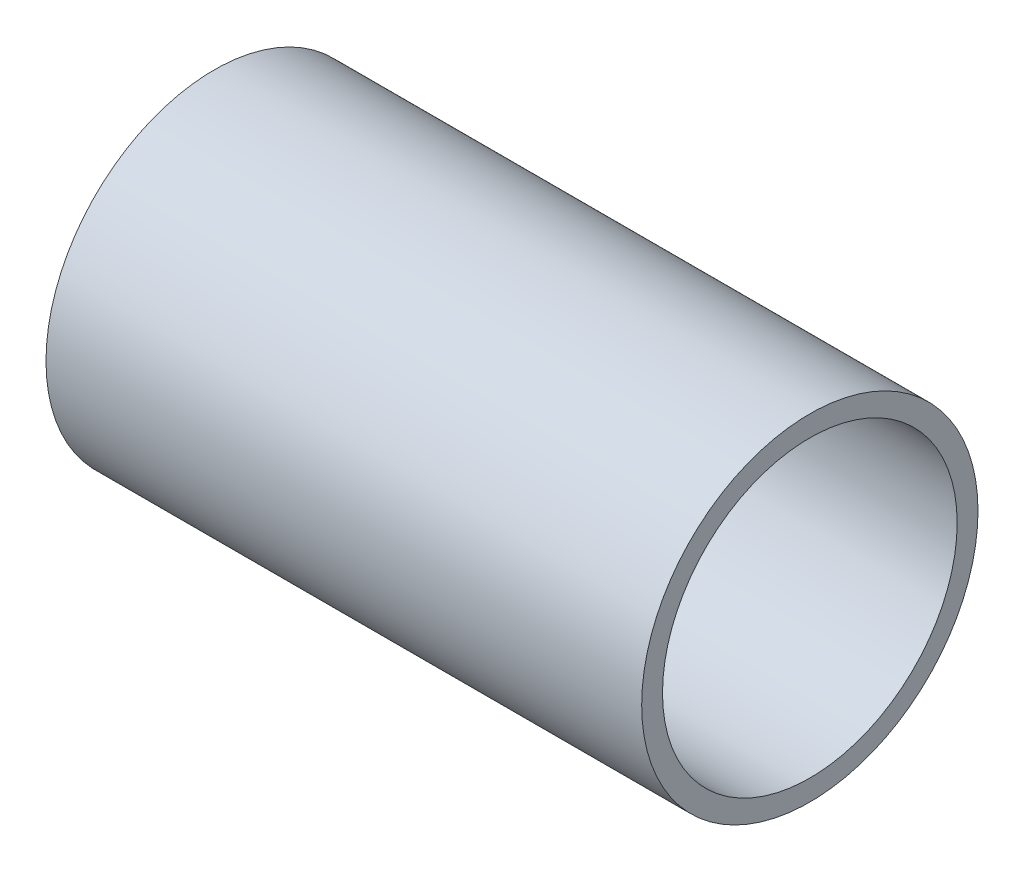
SolidWorks part; units mm, degrees
ref_plane "Front" through (0, 0, 0) normal (0, 0, 1) x (1, 0, 0)
ref_plane "Top" through (0, 0, 0) normal (0, 1, 0) x (1, 0, 0)
ref_plane "Right" through (0, 0, 0) normal (1, 0, 0) x (0, 0, -1)
sketch "Croquis1" plane through (0, 0, 0) normal (1, 0, 0) x (0, 0, -1)
  circle A0 centre (0, 0) radius 56.15
  circle A2 centre (0, 0) radius 64.0875
  dimension "D1" = 112.3
  dimension "D2" = 7.9375
extrude "Saliente-Extruir1" add sketch "Croquis1" along normal blind 227.0125
sketch "Croquis2" plane through (0, 0, 0) normal (0, 1, 0) x (1, 0, 0)
  line L0 (0, 0) -> (227.0125, 0) construction
  line L1 (227.0125, -64.0875) -> (227.0125, 64.0875) construction
  line L2 (113.5062, 64.0875) -> (113.5062, -64.0875) construction
  line L3 (227.0125, 64.0875) -> (0, 64.0875) construction
  line L4 (0, -64.0875) -> (227.0125, -64.0875) construction
  circle A0 centre (113.5062, 0) radius 42.5917
  circle A1 centre (113.5062, 0) radius 64.0875
